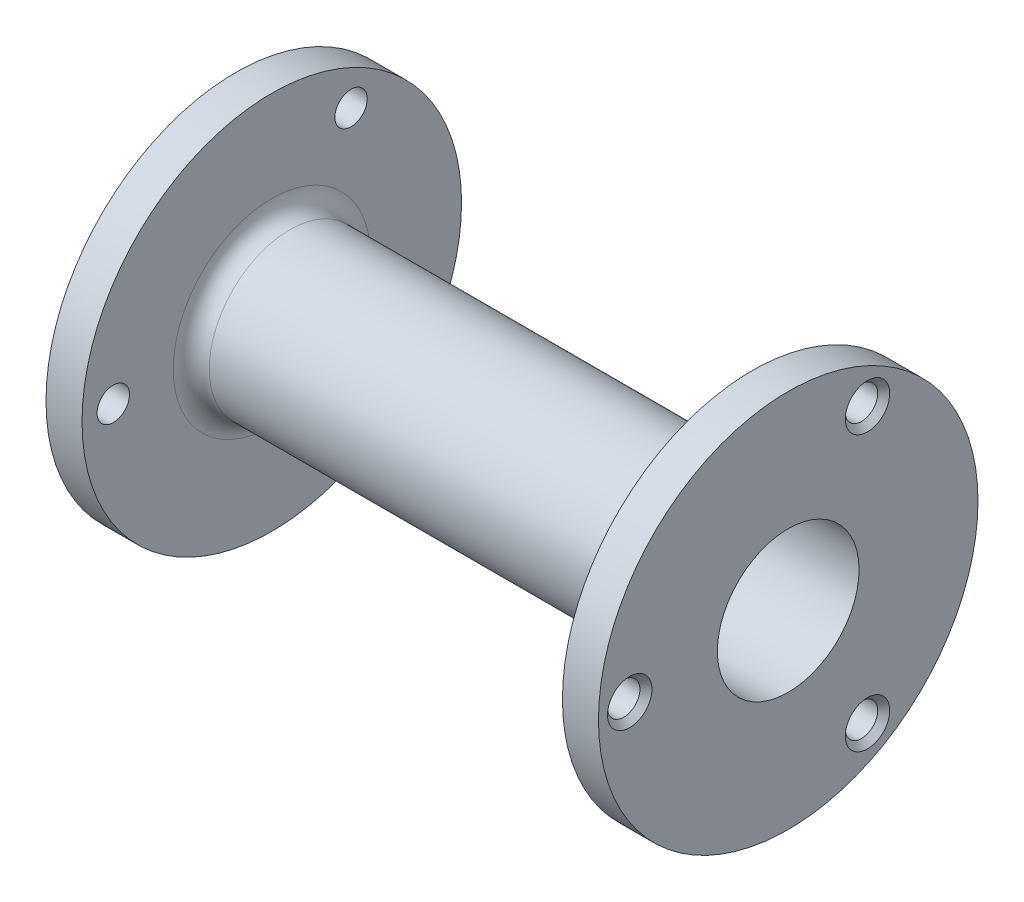
SolidWorks part; units mm, degrees
ref_plane "Front Plane" through (0, 0, 0) normal (0, 0, 1) x (1, 0, 0)
ref_plane "Top Plane" through (0, 0, 0) normal (0, 1, 0) x (1, 0, 0)
ref_plane "Right Plane" through (0, 0, 0) normal (1, 0, 0) x (0, 0, -1)
sketch "Sketch1" plane through (0, 0, 0) normal (0, 0, 1) x (1, 0, 0)
  line L0 (0, 5.9) -> (0, 15.8)
  line L1 (0, 0) -> (-13.4865, 0) construction
  line L2 (0, 15.8) -> (3, 15.8)
  line L3 (3, 15.8) -> (3, 8.21)
  line L4 (3, 5.9) -> (43, 5.9)
  line L5 (4.5, 6.71) -> (41.5, 6.71)
  line L6 (3, 5.9) -> (0, 5.9)
  line L7 (43, 8.21) -> (43, 15.8)
  line L8 (43, 15.8) -> (46, 15.8)
  line L9 (46, 15.8) -> (46, 5.9)
  line L10 (46, 5.9) -> (43, 5.9)
  arc A0 (41.5, 6.71) -> (43, 8.21) centre (41.5, 8.21) ccw
  arc A1 (4.5, 6.71) -> (3, 8.21) centre (4.5, 8.21) cw
  point P17 (3, 6.71)
  dimension "D1" = 11.8
  dimension "D2" = 3
  dimension "D6" = 1.5
  dimension "D3" = 31.6
  dimension "D4" = 0.81
  dimension "D5" = 40
revolve "Revolve1" add sketch "Sketch1" angle 360 about L1
sketch "Sketch3" plane through (46, 0, 0) normal (1, 0, 0) x (0, 0, -1)
  line L0 (-13.2, 0) -> (0, 0) construction
  circle A0 centre (-13.2, 0) radius 1.35
  circle A1 centre (0, 0) radius 15.8 construction
  circle A3 centre (6.6, 11.4315) radius 1.35
  circle A4 centre (6.6, -11.4315) radius 1.35
  point P4 (-15.8, 0)
  point P13 (0, 0)
  dimension "D1" = 13.2
  dimension "D2" = 2.7
  dimension "D3" = 3
extrude "Cut-Extrude1" cut sketch "Sketch3" against normal through all
chamfer "Chamfer1" distance 0.5 angle 45 6 edges at (46, 0, 11.85) (46, -11.4315, -7.95) (46, 11.4315, -7.95) (0, -11.4315, -7.95) (0, 11.4315, -7.95) (0, 0, 11.85)
